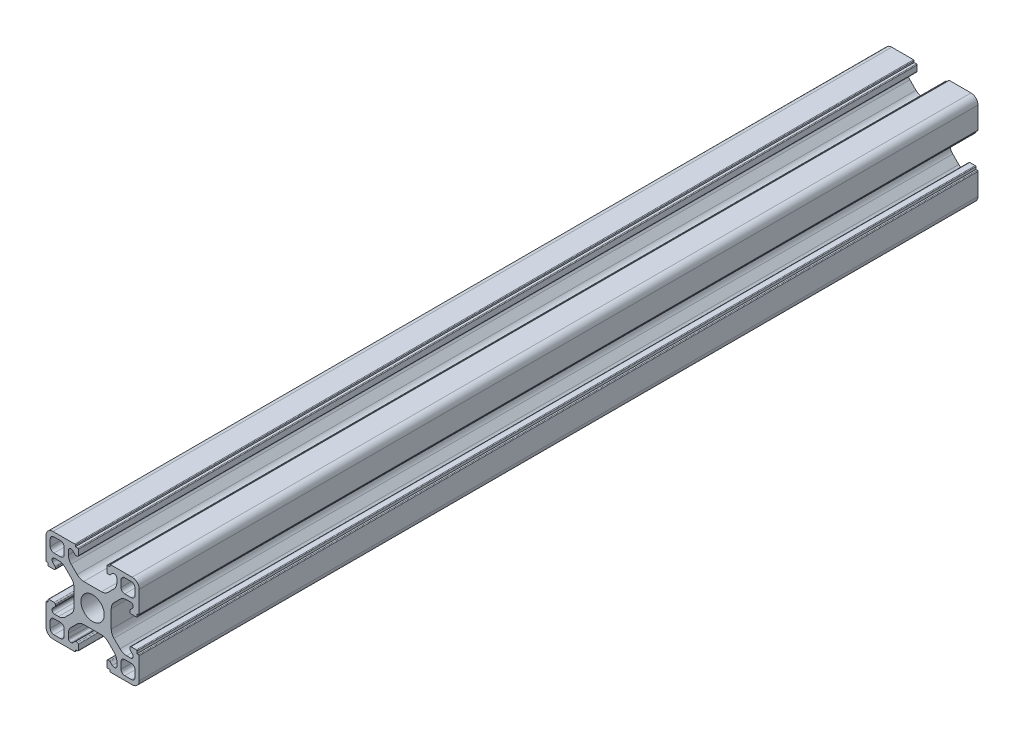
SolidWorks part; units mm, degrees
material "1060 Сплав"
ref_plane "Спереди" through (0, 0, 0) normal (0, 0, 1) x (1, 0, 0)
ref_plane "Сверху" through (0, 0, 0) normal (0, 1, 0) x (1, 0, 0)
ref_plane "Справа" through (0, 0, 0) normal (1, 0, 0) x (0, 0, -1)
sketch "Эскиз1" plane through (0, 0, 0) normal (0, 0, 1) x (1, 0, 0)
  line L0 (-22.0052, 70.3096) -> (-25.0052, 67.3096) construction
  line L1 (-31.1052, 65.2096) -> (-29.2064, 65.2096)
  line L2 (-31.1052, 61.2096) -> (-21.1052, 71.2096) construction
  line L3 (-23.5052, 68.8096) -> (-25.0052, 70.3096) construction
  line L4 (-27.7922, 65.7954) -> (-26.4909, 67.0967)
  line L5 (-24.2052, 67.3096) -> (-22.8052, 67.3096)
  line L6 (-25.0052, 68.1096) -> (-25.0052, 69.5096)
  line L7 (-22.8052, 70.3096) -> (-24.2052, 70.3096)
  line L8 (-25.9052, 69.4096) -> (-25.9052, 68.5109)
  line L9 (-27.3419, 69.2829) -> (-26.8616, 69.7632)
  line L10 (-27.9052, 70.7587) -> (-27.4052, 70.7587)
  line L11 (-27.5187, 69.2096) -> (-27.8052, 69.2096)
  line L12 (-26.508, 69.9096) -> (-26.4052, 69.9096)
  line L13 (-27.4052, 71.0596) -> (-27.4052, 70.7587)
  line L14 (-28.0552, 70.6087) -> (-28.0552, 69.4596)
  line L15 (-22.6052, 71.2096) -> (-27.2552, 71.2096)
  line L16 (-22.0052, 69.5096) -> (-22.0052, 68.1096)
  line L17 (-21.1052, 69.7096) -> (-21.1052, 65.0596)
  line L18 (-21.7061, 64.2596) -> (-22.8552, 64.2596)
  line L19 (-21.2552, 64.9096) -> (-21.5561, 64.9096)
  line L20 (-22.4052, 65.8068) -> (-22.4052, 65.9096)
  line L21 (-23.1052, 64.7961) -> (-23.1052, 64.5096)
  line L22 (-21.5561, 64.4096) -> (-21.5561, 64.9096)
  line L23 (-23.0319, 64.9729) -> (-22.5516, 65.4532)
  line L24 (-22.9052, 66.4096) -> (-23.8039, 66.4096)
  line L25 (-26.5194, 64.5226) -> (-25.2181, 65.8239)
  line L26 (-27.1052, 61.2096) -> (-27.1052, 63.1084)
  line L27 (-27.1052, 61.2096) -> (-27.1052, 59.3109)
  line L28 (-26.5194, 57.8967) -> (-25.2181, 56.5954)
  line L29 (-25.0052, 54.3096) -> (-25.0052, 52.9096)
  line L30 (-24.2052, 55.1096) -> (-22.8052, 55.1096)
  line L31 (-22.0052, 52.9096) -> (-22.0052, 54.3096)
  line L32 (-22.9052, 56.0096) -> (-23.8039, 56.0096)
  line L33 (-23.0319, 57.4464) -> (-22.5516, 56.9661)
  line L34 (-21.5561, 58.0096) -> (-21.5561, 57.5096)
  line L35 (-23.1052, 57.6232) -> (-23.1052, 57.9096)
  line L36 (-22.4052, 56.6125) -> (-22.4052, 56.5096)
  line L37 (-21.2552, 57.5096) -> (-21.5561, 57.5096)
  line L38 (-21.7061, 58.1596) -> (-22.8552, 58.1596)
  line L39 (-21.1052, 52.7096) -> (-21.1052, 57.3596)
  line L40 (-22.8052, 52.1096) -> (-24.2052, 52.1096)
  line L41 (-22.6052, 51.2096) -> (-27.2552, 51.2096)
  line L42 (-28.0552, 51.8106) -> (-28.0552, 52.9596)
  line L43 (-27.4052, 51.3596) -> (-27.4052, 51.6606)
  line L44 (-26.508, 52.5096) -> (-26.4052, 52.5096)
  line L45 (-27.5187, 53.2096) -> (-27.8052, 53.2096)
  line L46 (-27.9052, 51.6606) -> (-27.4052, 51.6606)
  line L47 (-27.3419, 53.1364) -> (-26.8616, 52.6561)
  line L48 (-25.9052, 53.0096) -> (-25.9052, 53.9084)
  line L49 (-27.7922, 56.6239) -> (-26.4909, 55.3226)
  line L50 (-31.1052, 57.2096) -> (-29.2064, 57.2096)
  line L51 (-22.0052, 52.1096) -> (-25.0052, 55.1096) construction
  line L52 (-31.1052, 61.2096) -> (-21.1052, 51.2096) construction
  line L53 (-23.5052, 53.6096) -> (-22.0052, 55.1096) construction
  line L54 (-31.1052, 57.2096) -> (-33.0039, 57.2096)
  line L55 (-34.4181, 56.6239) -> (-35.7194, 55.3226)
  line L56 (-38.0052, 55.1096) -> (-39.4052, 55.1096)
  line L57 (-37.2052, 54.3096) -> (-37.2052, 52.9096)
  line L58 (-39.4052, 52.1096) -> (-38.0052, 52.1096)
  line L59 (-36.3052, 53.0096) -> (-36.3052, 53.9084)
  line L60 (-34.8684, 53.1364) -> (-35.3487, 52.6561)
  line L61 (-34.3052, 51.6606) -> (-34.8052, 51.6606)
  line L62 (-34.6916, 53.2096) -> (-34.4052, 53.2096)
  line L63 (-35.7023, 52.5096) -> (-35.8052, 52.5096)
  line L64 (-34.8052, 51.3596) -> (-34.8052, 51.6606)
  line L65 (-34.1552, 51.8106) -> (-34.1552, 52.9596)
  line L66 (-39.6052, 51.2096) -> (-34.9552, 51.2096)
  line L67 (-40.2052, 52.9096) -> (-40.2052, 54.3096)
  line L68 (-41.1052, 52.7096) -> (-41.1052, 57.3596)
  line L69 (-40.5042, 58.1596) -> (-39.3552, 58.1596)
  line L70 (-40.9552, 57.5096) -> (-40.6542, 57.5096)
  line L71 (-39.8052, 56.6125) -> (-39.8052, 56.5096)
  line L72 (-39.1052, 57.6232) -> (-39.1052, 57.9096)
  line L73 (-40.6542, 58.0096) -> (-40.6542, 57.5096)
  line L74 (-39.1784, 57.4464) -> (-39.6587, 56.9661)
  line L75 (-39.3052, 56.0096) -> (-38.4064, 56.0096)
  line L76 (-35.6909, 57.8967) -> (-36.9922, 56.5954)
  line L77 (-35.1052, 61.2096) -> (-35.1052, 59.3109)
  line L78 (-40.2052, 52.1096) -> (-37.2052, 55.1096) construction
  line L79 (-31.1052, 61.2096) -> (-41.1052, 51.2096) construction
  line L80 (-38.7052, 53.6096) -> (-37.2052, 52.1096) construction
  line L81 (-35.1052, 61.2096) -> (-35.1052, 63.1084)
  line L82 (-35.6909, 64.5226) -> (-36.9922, 65.8239)
  line L83 (-37.2052, 68.1096) -> (-37.2052, 69.5096)
  line L84 (-38.0052, 67.3096) -> (-39.4052, 67.3096)
  line L85 (-40.2052, 69.5096) -> (-40.2052, 68.1096)
  line L86 (-39.3052, 66.4096) -> (-38.4064, 66.4096)
  line L87 (-39.1784, 64.9729) -> (-39.6587, 65.4532)
  line L88 (-40.6542, 64.4096) -> (-40.6542, 64.9096)
  line L89 (-39.1052, 64.7961) -> (-39.1052, 64.5096)
  line L90 (-39.8052, 65.8068) -> (-39.8052, 65.9096)
  line L91 (-40.9552, 64.9096) -> (-40.6542, 64.9096)
  line L92 (-40.5042, 64.2596) -> (-39.3552, 64.2596)
  line L93 (-41.1052, 69.7096) -> (-41.1052, 65.0596)
  line L94 (-39.4052, 70.3096) -> (-38.0052, 70.3096)
  line L95 (-39.6052, 71.2096) -> (-34.9552, 71.2096)
  line L96 (-34.1552, 70.6087) -> (-34.1552, 69.4596)
  line L97 (-34.8052, 71.0596) -> (-34.8052, 70.7587)
  line L98 (-35.7023, 69.9096) -> (-35.8052, 69.9096)
  line L99 (-34.6916, 69.2096) -> (-34.4052, 69.2096)
  line L100 (-34.3052, 70.7587) -> (-34.8052, 70.7587)
  line L101 (-34.8684, 69.2829) -> (-35.3487, 69.7632)
  line L102 (-36.3052, 69.4096) -> (-36.3052, 68.5109)
  line L103 (-34.4181, 65.7954) -> (-35.7194, 67.0967)
  line L104 (-31.1052, 65.2096) -> (-33.0039, 65.2096)
  line L105 (-42.8692, 61.2096) -> (-19.6008, 61.2096) construction
  line L106 (-40.2052, 70.3096) -> (-37.2052, 67.3096) construction
  line L107 (-31.1052, 49.1232) -> (-31.1052, 71.9286) construction
  line L108 (-31.1052, 61.2096) -> (-41.1052, 71.2096) construction
  line L109 (-38.7052, 68.8096) -> (-40.2052, 67.3096) construction
  arc A0 (-22.0052, 69.5096) -> (-22.8052, 70.3096) centre (-22.8052, 69.5096) ccw
  arc A1 (-24.2052, 70.3096) -> (-25.0052, 69.5096) centre (-24.2052, 69.5096) ccw
  arc A2 (-24.2052, 67.3096) -> (-25.0052, 68.1096) centre (-24.2052, 68.1096) cw
  arc A3 (-22.6052, 71.2096) -> (-21.1052, 69.7096) centre (-22.6052, 69.7096) cw
  arc A4 (-27.9052, 70.7587) -> (-28.0552, 70.6087) centre (-27.9052, 70.6087) ccw
  arc A5 (-27.2552, 71.2096) -> (-27.4052, 71.0596) centre (-27.2552, 71.0596) ccw
  arc A6 (-27.5187, 69.2096) -> (-27.3419, 69.2829) centre (-27.5187, 69.4596) ccw
  arc A7 (-27.8052, 69.2096) -> (-28.0552, 69.4596) centre (-27.8052, 69.4596) cw
  arc A8 (-26.8616, 69.7632) -> (-26.508, 69.9096) centre (-26.508, 69.4096) cw
  arc A9 (-26.4052, 69.9096) -> (-25.9052, 69.4096) centre (-26.4052, 69.4096) cw
  arc A10 (-28.6052, 61.2096) -> (-31.1052, 63.7096) centre (-31.1052, 61.2096) ccw
  arc A11 (-29.2064, 65.2096) -> (-27.7922, 65.7954) centre (-29.2064, 67.2096) ccw
  arc A12 (-25.9052, 68.5109) -> (-26.4909, 67.0967) centre (-27.9052, 68.5109) cw
  arc A13 (-22.0052, 68.1096) -> (-22.8052, 67.3096) centre (-22.8052, 68.1096) cw
  arc A14 (-22.4052, 65.9096) -> (-22.9052, 66.4096) centre (-22.9052, 65.9096) ccw
  arc A15 (-22.5516, 65.4532) -> (-22.4052, 65.8068) centre (-22.9052, 65.8068) ccw
  arc A16 (-23.1052, 64.5096) -> (-22.8552, 64.2596) centre (-22.8552, 64.5096) ccw
  arc A17 (-23.1052, 64.7961) -> (-23.0319, 64.9729) centre (-22.8552, 64.7961) cw
  arc A18 (-21.1052, 65.0596) -> (-21.2552, 64.9096) centre (-21.2552, 65.0596) cw
  arc A19 (-21.5561, 64.4096) -> (-21.7061, 64.2596) centre (-21.7061, 64.4096) cw
  arc A20 (-23.8039, 66.4096) -> (-25.2181, 65.8239) centre (-23.8039, 64.4096) ccw
  arc A21 (-27.1052, 63.1084) -> (-26.5194, 64.5226) centre (-25.1052, 63.1084) cw
  arc A22 (-22.8052, 52.1096) -> (-22.0052, 52.9096) centre (-22.8052, 52.9096) ccw
  arc A23 (-22.0052, 54.3096) -> (-22.8052, 55.1096) centre (-22.8052, 54.3096) ccw
  arc A24 (-25.0052, 54.3096) -> (-24.2052, 55.1096) centre (-24.2052, 54.3096) cw
  arc A25 (-21.1052, 52.7096) -> (-22.6052, 51.2096) centre (-22.6052, 52.7096) cw
  arc A26 (-21.5561, 58.0096) -> (-21.7061, 58.1596) centre (-21.7061, 58.0096) ccw
  arc A27 (-21.1052, 57.3596) -> (-21.2552, 57.5096) centre (-21.2552, 57.3596) ccw
  arc A28 (-23.1052, 57.6232) -> (-23.0319, 57.4464) centre (-22.8552, 57.6232) ccw
  arc A29 (-23.1052, 57.9096) -> (-22.8552, 58.1596) centre (-22.8552, 57.9096) cw
  arc A30 (-22.5516, 56.9661) -> (-22.4052, 56.6125) centre (-22.9052, 56.6125) cw
  arc A31 (-22.4052, 56.5096) -> (-22.9052, 56.0096) centre (-22.9052, 56.5096) cw
  arc A32 (-31.1052, 58.7096) -> (-28.6052, 61.2096) centre (-31.1052, 61.2096) ccw
  arc A33 (-27.1052, 59.3109) -> (-26.5194, 57.8967) centre (-25.1052, 59.3109) ccw
  arc A34 (-23.8039, 56.0096) -> (-25.2181, 56.5954) centre (-23.8039, 58.0096) cw
  arc A35 (-24.2052, 52.1096) -> (-25.0052, 52.9096) centre (-24.2052, 52.9096) cw
  arc A36 (-26.4052, 52.5096) -> (-25.9052, 53.0096) centre (-26.4052, 53.0096) ccw
  arc A37 (-26.8616, 52.6561) -> (-26.508, 52.5096) centre (-26.508, 53.0096) ccw
  arc A38 (-27.8052, 53.2096) -> (-28.0552, 52.9596) centre (-27.8052, 52.9596) ccw
  arc A39 (-27.5187, 53.2096) -> (-27.3419, 53.1364) centre (-27.5187, 52.9596) cw
  arc A40 (-27.2552, 51.2096) -> (-27.4052, 51.3596) centre (-27.2552, 51.3596) cw
  arc A41 (-27.9052, 51.6606) -> (-28.0552, 51.8106) centre (-27.9052, 51.8106) cw
  arc A42 (-25.9052, 53.9084) -> (-26.4909, 55.3226) centre (-27.9052, 53.9084) ccw
  arc A43 (-29.2064, 57.2096) -> (-27.7922, 56.6239) centre (-29.2064, 55.2096) cw
  arc A44 (-40.2052, 52.9096) -> (-39.4052, 52.1096) centre (-39.4052, 52.9096) ccw
  arc A45 (-38.0052, 52.1096) -> (-37.2052, 52.9096) centre (-38.0052, 52.9096) ccw
  arc A46 (-38.0052, 55.1096) -> (-37.2052, 54.3096) centre (-38.0052, 54.3096) cw
  arc A47 (-39.6052, 51.2096) -> (-41.1052, 52.7096) centre (-39.6052, 52.7096) cw
  arc A48 (-34.3052, 51.6606) -> (-34.1552, 51.8106) centre (-34.3052, 51.8106) ccw
  arc A49 (-34.9552, 51.2096) -> (-34.8052, 51.3596) centre (-34.9552, 51.3596) ccw
  arc A50 (-34.6916, 53.2096) -> (-34.8684, 53.1364) centre (-34.6916, 52.9596) ccw
  arc A51 (-34.4052, 53.2096) -> (-34.1552, 52.9596) centre (-34.4052, 52.9596) cw
  arc A52 (-35.3487, 52.6561) -> (-35.7023, 52.5096) centre (-35.7023, 53.0096) cw
  arc A53 (-35.8052, 52.5096) -> (-36.3052, 53.0096) centre (-35.8052, 53.0096) cw
  arc A54 (-33.6052, 61.2096) -> (-31.1052, 58.7096) centre (-31.1052, 61.2096) ccw
  arc A55 (-33.0039, 57.2096) -> (-34.4181, 56.6239) centre (-33.0039, 55.2096) ccw
  arc A56 (-36.3052, 53.9084) -> (-35.7194, 55.3226) centre (-34.3052, 53.9084) cw
  arc A57 (-40.2052, 54.3096) -> (-39.4052, 55.1096) centre (-39.4052, 54.3096) cw
  arc A58 (-39.8052, 56.5096) -> (-39.3052, 56.0096) centre (-39.3052, 56.5096) ccw
  arc A59 (-39.6587, 56.9661) -> (-39.8052, 56.6125) centre (-39.3052, 56.6125) ccw
  arc A60 (-39.1052, 57.9096) -> (-39.3552, 58.1596) centre (-39.3552, 57.9096) ccw
  arc A61 (-39.1052, 57.6232) -> (-39.1784, 57.4464) centre (-39.3552, 57.6232) cw
  arc A62 (-41.1052, 57.3596) -> (-40.9552, 57.5096) centre (-40.9552, 57.3596) cw
  arc A63 (-40.6542, 58.0096) -> (-40.5042, 58.1596) centre (-40.5042, 58.0096) cw
  arc A64 (-38.4064, 56.0096) -> (-36.9922, 56.5954) centre (-38.4064, 58.0096) ccw
  arc A65 (-35.1052, 59.3109) -> (-35.6909, 57.8967) centre (-37.1052, 59.3109) cw
  arc A66 (-39.4052, 70.3096) -> (-40.2052, 69.5096) centre (-39.4052, 69.5096) ccw
  arc A67 (-40.2052, 68.1096) -> (-39.4052, 67.3096) centre (-39.4052, 68.1096) ccw
  arc A68 (-37.2052, 68.1096) -> (-38.0052, 67.3096) centre (-38.0052, 68.1096) cw
  arc A69 (-41.1052, 69.7096) -> (-39.6052, 71.2096) centre (-39.6052, 69.7096) cw
  arc A70 (-40.6542, 64.4096) -> (-40.5042, 64.2596) centre (-40.5042, 64.4096) ccw
  arc A71 (-41.1052, 65.0596) -> (-40.9552, 64.9096) centre (-40.9552, 65.0596) ccw
  arc A72 (-39.1052, 64.7961) -> (-39.1784, 64.9729) centre (-39.3552, 64.7961) ccw
  arc A73 (-39.1052, 64.5096) -> (-39.3552, 64.2596) centre (-39.3552, 64.5096) cw
  arc A74 (-39.6587, 65.4532) -> (-39.8052, 65.8068) centre (-39.3052, 65.8068) cw
  arc A75 (-39.8052, 65.9096) -> (-39.3052, 66.4096) centre (-39.3052, 65.9096) cw
  arc A76 (-31.1052, 63.7096) -> (-33.6052, 61.2096) centre (-31.1052, 61.2096) ccw
  arc A77 (-35.1052, 63.1084) -> (-35.6909, 64.5226) centre (-37.1052, 63.1084) ccw
  arc A78 (-38.4064, 66.4096) -> (-36.9922, 65.8239) centre (-38.4064, 64.4096) cw
  arc A79 (-38.0052, 70.3096) -> (-37.2052, 69.5096) centre (-38.0052, 69.5096) cw
  arc A80 (-35.8052, 69.9096) -> (-36.3052, 69.4096) centre (-35.8052, 69.4096) ccw
  arc A81 (-35.3487, 69.7632) -> (-35.7023, 69.9096) centre (-35.7023, 69.4096) ccw
  arc A82 (-34.4052, 69.2096) -> (-34.1552, 69.4596) centre (-34.4052, 69.4596) ccw
  arc A83 (-34.6916, 69.2096) -> (-34.8684, 69.2829) centre (-34.6916, 69.4596) cw
  arc A84 (-34.9552, 71.2096) -> (-34.8052, 71.0596) centre (-34.9552, 71.0596) cw
  arc A85 (-34.3052, 70.7587) -> (-34.1552, 70.6087) centre (-34.3052, 70.6087) cw
  arc A86 (-36.3052, 68.5109) -> (-35.7194, 67.0967) centre (-34.3052, 68.5109) ccw
  arc A87 (-33.0039, 65.2096) -> (-34.4181, 65.7954) centre (-33.0039, 67.2096) cw
  point P0 (-31.1052, 61.2096)
  point P9 (-31.1052, 61.2096)
  point P40 (-22.4052, 64.9096)
  point P93 (-27.4052, 52.5096)
  point P144 (-27.4052, 69.9096)
  point P152 (-22.4052, 57.5096)
  point P153 (-31.1052, 57.2854)
  point P154 (-31.1052, 61.2096)
  point P189 (-39.8052, 57.5096)
  point P228 (-34.8052, 52.5096)
  point P229 (-35.0294, 61.2096)
  point P230 (-31.1052, 61.2096)
  point P268 (-34.8052, 69.9096)
  point P273 (-27.1809, 61.2096)
  point P306 (-39.8052, 64.9096)
  point P307 (-31.1052, 65.1339)
  point P309 (-31.1052, 61.2096)
  dimension "D3" = 5
  dimension "D6" = 2
  dimension "D1" = 2
  dimension "D2" = 6
  dimension "D4" = 4
  dimension "D5" = 0.9
extrude "Бобышка-Вытянуть1" add sketch "Эскиз1" along normal blind 180
